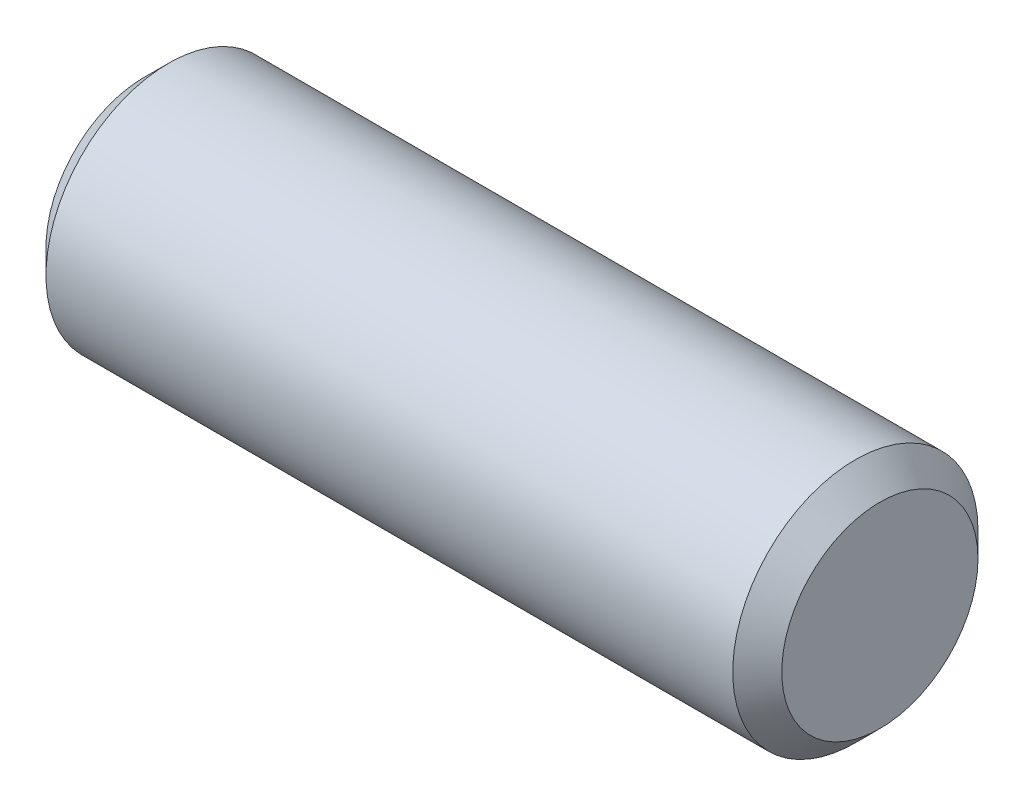
SolidWorks part; units mm, degrees
ref_plane "Front" through (0, 0, 0) normal (0, 0, 1) x (1, 0, 0)
ref_plane "Top" through (0, 0, 0) normal (0, 1, 0) x (1, 0, 0)
ref_plane "Right" through (0, 0, 0) normal (1, 0, 0) x (0, 0, -1)
sketch "Sketch1" plane through (0, 0, 0) normal (0, 0, 1) x (1, 0, 0)
  line L0 (-7.1437, 0) -> (7.1437, 0) construction
  line L1 (7.1438, 2.3813) -> (7.1438, -2.3813) construction
  line L2 (-7.1437, 2.3813) -> (-7.1437, -2.3813) construction
  dimension "Length" = 14.2875
  dimension "Diameter" = 4.7625
sketch "Sketch2" plane through (0, 0, 0) normal (1, 0, 0) x (0, 0, -1)
  circle A0 centre (0, 0) radius 2.3813
extrude "Extrude1" add sketch "Sketch2" against normal up to vertex (7.1437 mm away) and the other way up to vertex (7.1437 mm away) up to point (-7.1437, 2.3813, 0) other way up to point (7.1438, 2.3813, 0)
chamfer "Chamfer1" distance 0.4763 angle 45 2 edges at (7.1438, 0, -2.3813) (-7.1437, 0, -2.3813)
equation "\"D1@Chamfer1\" = \"Diameter@Sketch1\"*.1"
